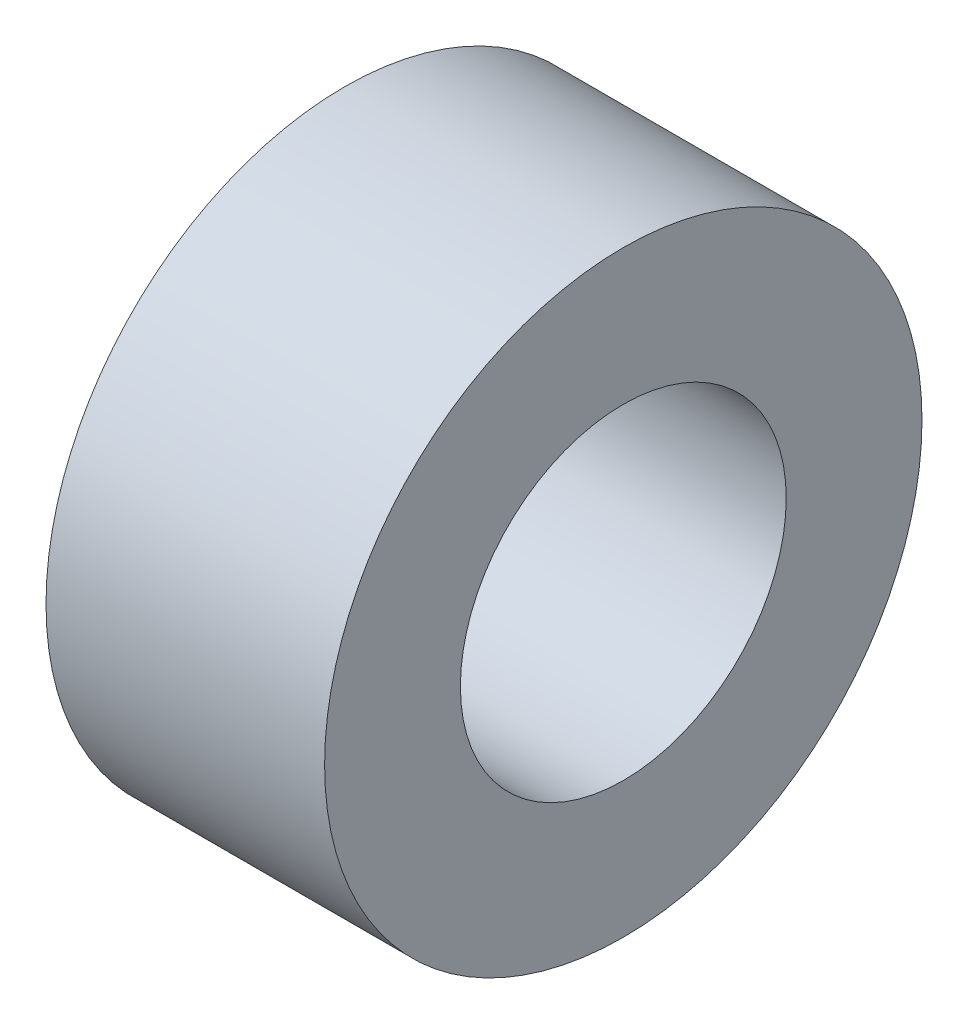
SolidWorks part; units mm, degrees
ref_plane "前视基准面" through (0, 0, 0) normal (0, 0, 1) x (1, 0, 0)
ref_plane "上视基准面" through (0, 0, 0) normal (0, 1, 0) x (1, 0, 0)
ref_plane "右视基准面" through (0, 0, 0) normal (1, 0, 0) x (0, 0, -1)
sketch "草图1" plane through (0, 0, 0) normal (1, 0, 0) x (0, 0, -1)
  circle A0 centre (0, 0) radius 3
  circle A1 centre (0, 0) radius 5.5
extrude "凸台-拉伸1" add sketch "草图1" along normal blind 5.13
